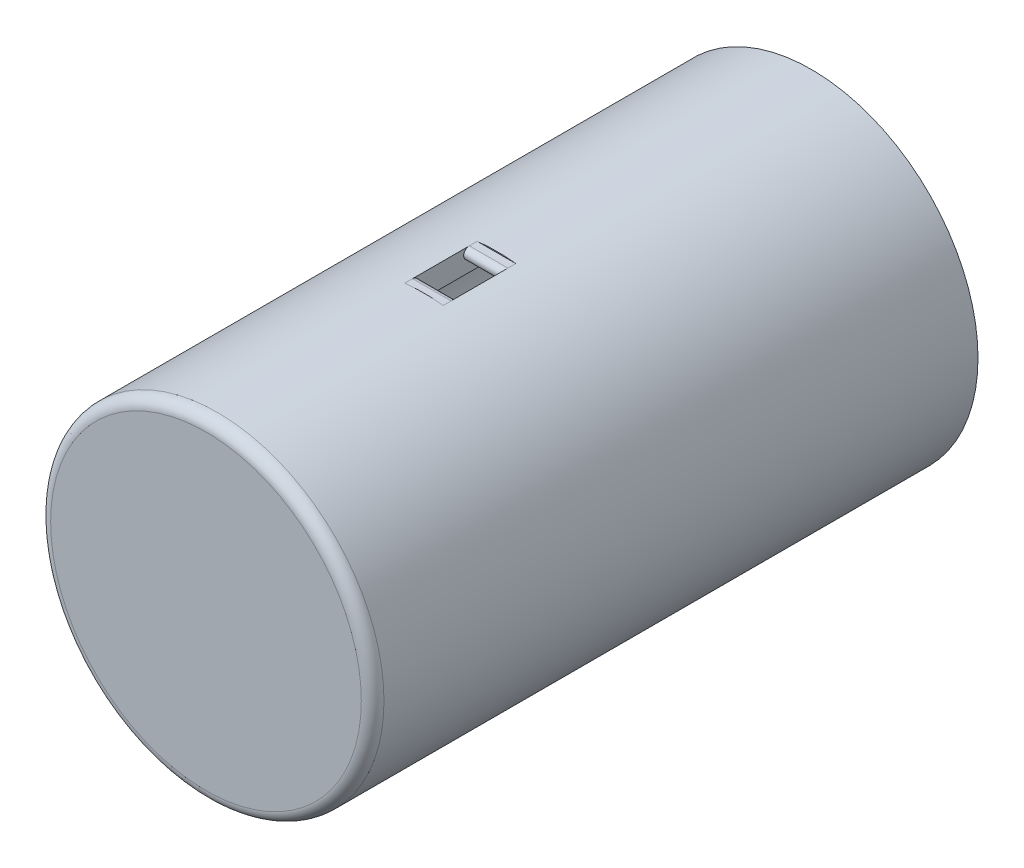
SolidWorks part; units mm, degrees
ref_plane "Front Plane" through (0, 0, 0) normal (1, 0, 0) x (0, 1, 0)
ref_plane "Top Plane" through (0, 0, 0) normal (0, 0, 1) x (0, 1, 0)
ref_plane "Right Plane" through (0, 0, 0) normal (0, 1, 0) x (-1, 0, 0)
sketch "Sketch1" plane through (0, 0, 0) normal (0, 0, 1) x (0, 1, 0)
  circle A0 centre (0, 0) radius 14.7
  dimension "D1" = 29.4
extrude "Boss-Extrude1" add sketch "Sketch1" along normal blind 50
sketch "Sketch2" plane through (0, 0, 50) normal (0, 0, 1) x (1, 0, 0)
  circle A0 centre (0, 0) radius 12.7
  circle A1 centre (0, 0) radius 14.7 construction
  dimension "D2" = 25.4
  dimension "D1" = 2
extrude "Cut-Extrude1" cut sketch "Sketch2" against normal up to next
sketch "Sketch3" plane through (0, 0, 0) normal (1, 0, 0) x (0, 1, 0)
  line L0 (0, 50) -> (0, 0) construction
  line L1 (14.7, 50) -> (-14.7, 50) construction
ref_plane "Plane1" through (0, -12.7, 0) normal (0, 1, 0) x (-1, 0, 0)
sketch "Sketch4" plane through (0, -12.7, 0) normal (0, 1, 0) x (-1, 0, 0)
  line L0 (0, 50) -> (0, 0) construction
  line L1 (-1.7, 0) -> (1.7, 0)
  line L2 (-1.7, 0) -> (-1.7, 50)
  line L3 (-1.7, 50) -> (1.7, 50)
  line L4 (1.7, 0) -> (1.7, 50)
  line L5 (-1.7, 0) -> (1.7, 50) construction
  line L6 (-1.7, 50) -> (1.7, 0) construction
  line L7 (14.7, 50) -> (-14.7, 50) construction
  point P0 (0, 25)
  dimension "D1" = 3.4
extrude "Cut-Extrude2" cut sketch "Sketch4" along normal up to next
sketch "Sketch5" plane through (0, -12.7, 0) normal (0, 1, 0) x (-1, 0, 0)
  line L0 (-1.7, 50) -> (-1.7, 0) construction
  line L1 (-1.7, 27.7738) -> (1.7, 27.7738)
  line L2 (-1.7, 27.7738) -> (-1.7, 34.1738)
  line L3 (-1.7, 34.1738) -> (1.7, 34.1738)
  line L4 (1.7, 27.7738) -> (1.7, 34.1738)
  line L5 (1.7, 0) -> (1.7, 50) construction
  line L6 (-1.7, 0) -> (1.7, 0) construction
  dimension "D1" = 27.7738
  dimension "D2" = 6.4
extrude "Cut-Extrude3" cut sketch "Sketch5" against normal blind 2
sketch "Sketch6" plane through (-1.7, 0, 0) normal (1, 0, 0) x (0, 1, 0)
  line L0 (-14.6014, 27.7738) -> (-12.7, 27.7738)
  line L1 (-12.7, -7.15) -> (-12.7, 7.15) construction
  line L2 (-12.7, 27.7738) -> (-14.6014, 29.6752)
  line L3 (-14.6014, 34.1738) -> (-14.6014, 27.7738) construction
  line L4 (-14.6014, 29.6752) -> (-14.6014, 27.7738)
  line L5 (-14.6014, 34.1738) -> (-12.7, 34.1738)
  line L6 (-12.7, 34.1738) -> (-14.6014, 32.2725)
  line L7 (-14.6014, 32.2725) -> (-14.6014, 34.1738)
  dimension "D1" = 45
  dimension "D2" = 45
extrude "Boss-Extrude2" add sketch "Sketch6" along normal up to next
ref_plane "Plane2" through (0, 12.7, 0) normal (0, -1, 0) x (1, 0, 0)
sketch "Sketch7" plane through (0, 12.7, 0) normal (0, -1, 0) x (1, 0, 0)
  line L0 (0, 50) -> (0, 0) construction
  line L1 (-1.7, 0) -> (1.7, 0)
  line L2 (-1.7, 0) -> (-1.7, 50)
  line L3 (-1.7, 50) -> (1.7, 50)
  line L4 (1.7, 0) -> (1.7, 50)
  line L5 (-1.7, 0) -> (1.7, 50) construction
  line L6 (-1.7, 50) -> (1.7, 0) construction
  line L7 (14.7, 50) -> (-14.7, 50) construction
  point P0 (0, 25)
  dimension "D1" = 3.4
extrude "Cut-Extrude4" cut sketch "Sketch7" along normal up to next
sketch "Sketch8" plane through (0, 12.7, 0) normal (0, -1, 0) x (1, 0, 0)
  line L1 (-1.7, 34.1738) -> (1.7, 34.1738)
  line L2 (-1.7, 34.1738) -> (-1.7, 27.7738)
  line L3 (-1.7, 27.7738) -> (1.7, 27.7738)
  line L4 (1.7, 34.1738) -> (1.7, 27.7738)
extrude "Cut-Extrude5" cut sketch "Sketch8" against normal blind 2
sketch "Sketch9" plane through (-1.7, 0, 0) normal (1, 0, 0) x (0, 1, 0)
  line L0 (14.6014, 34.1738) -> (14.6014, 32.2725)
  line L1 (14.6014, 27.7738) -> (14.6014, 34.1738) construction
  line L2 (14.6014, 32.2725) -> (12.7, 34.1738)
  line L3 (12.7, 7.15) -> (12.7, -7.15) construction
  line L4 (12.7, 34.1738) -> (14.6014, 34.1738)
  line L5 (14.6014, 27.7738) -> (14.6014, 29.6752)
  line L6 (14.6014, 29.6752) -> (12.7, 27.7738)
  line L7 (12.7, 27.7738) -> (14.6014, 27.7738)
  dimension "D1" = 45
  dimension "D2" = 45
extrude "Boss-Extrude3" add sketch "Sketch9" along normal up to next
sketch "Sketch10" plane through (0, 0, 50) normal (0, 0, 1) x (1, 0, 0)
  circle A0 centre (0, 0) radius 14.7
extrude "Boss-Extrude4" add sketch "Sketch10" along normal blind 3.4
fillet "Fillet1" radius 0.5 8 edges at (0, -12.7, 27.7738) (0, -14.6014, 29.6752) (0, -14.6014, 32.2725) (0, -12.7, 34.1738) (0, 12.7, 27.7738) (0, 14.6014, 29.6752) (0, 12.7, 34.1738) (0, 14.6014, 32.2725)
fillet "Fillet2" radius 1 1 edges at (14.7, 0, 53.4)
equation "\"length\"= ( ( \"base2\" * ( \"height\" ^ 3 ) * \"delta\" * \"E\" ) / ( 6 * 0.67 * \"force\" ) ) ^ ( 1 / 3 )"
equation "\"height\"= 2"
equation "\"delta\"= 2"
equation "\"force\"= 1.5"
equation "\"E\"= 2750"
equation "\"diameter\"= 25mm + 2 * 2"
equation "\"t\"= 4mm"
equation "\"base\"=3.4"
equation "\"flex_len\"=6.4"
equation "\"cap_height\"= 50"
equation "\"clearance\"= 2"
equation "\"D1@Sketch1\"=\"diameter\"+0.4"
equation "\"D1@Boss-Extrude1\"=\"cap_height\""
equation "\"D1@Sketch2\"=\"clearance\""
equation "\"D1@Sketch4\"=\"base\""
equation "\"D1@Sketch5\"=\"length\"-0.2"
equation "\"D2@Sketch5\"=\"flex_len\""
equation "\"D1@Cut-Extrude3\"=\"delta\""
equation "\"D1@Sketch7\"=\"base\""
equation "\"D1@Cut-Extrude5\"=\"delta\""
equation "\"D1@Boss-Extrude4\"=\"base\""
equation "\"base2\"= 3"
